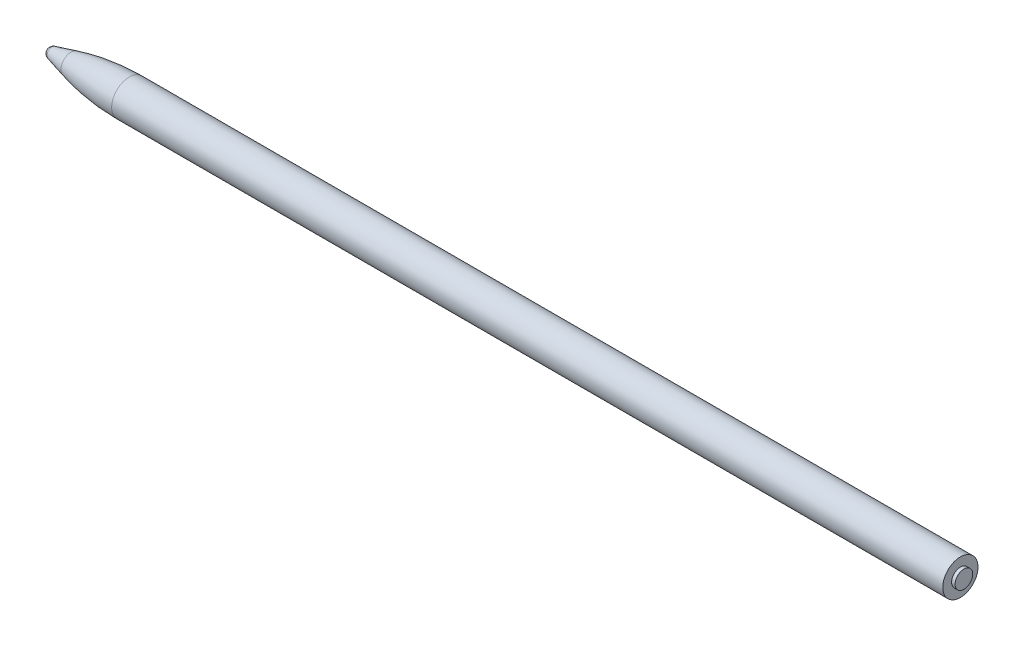
SolidWorks part; units mm, degrees
ref_plane "前视基准面" through (0, 0, 0) normal (0, 0, 1) x (1, 0, 0)
ref_plane "上视基准面" through (0, 0, 0) normal (0, 1, 0) x (1, 0, 0)
ref_plane "右视基准面" through (0, 0, 0) normal (1, 0, 0) x (0, 0, -1)
other "Configuration Table"
sketch "草图1" plane through (0, 0, 0) normal (0, 0, 1) x (1, 0, 0)
  line L6 (0, 0) -> (-52, 0) construction
  line L7 (0, 0) -> (0, 0.5)
  line L8 (0, 0.5) -> (-0.2, 0.5)
  line L9 (-0.2, 0.5) -> (-0.2, 1)
  line L10 (-0.2, 1) -> (-47.3955, 1)
  line L11 (-50.7, 0.573) -> (-51.7763, 0.2901)
  line L12 (0, 0) -> (-52, 0)
  arc A2 (-47.3955, 1) -> (-50.7, 0.573) centre (-47.3955, -12) ccw
  arc A3 (-51.7763, 0.2901) -> (-52, 0) centre (-51.7, 0) ccw
  point P2 (0, 0)
  point P12 (0, 0)
  point P13 (0, 0)
  dimension "D4" = 13
  dimension "D2" = 0.3
  dimension "D1" = 52
  dimension "D3" = 1
  dimension "D5" = 1
  dimension "D6" = 2
  dimension "D7" = 0.2
revolve "旋转1" add sketch "草图1" angle 360 about L6
